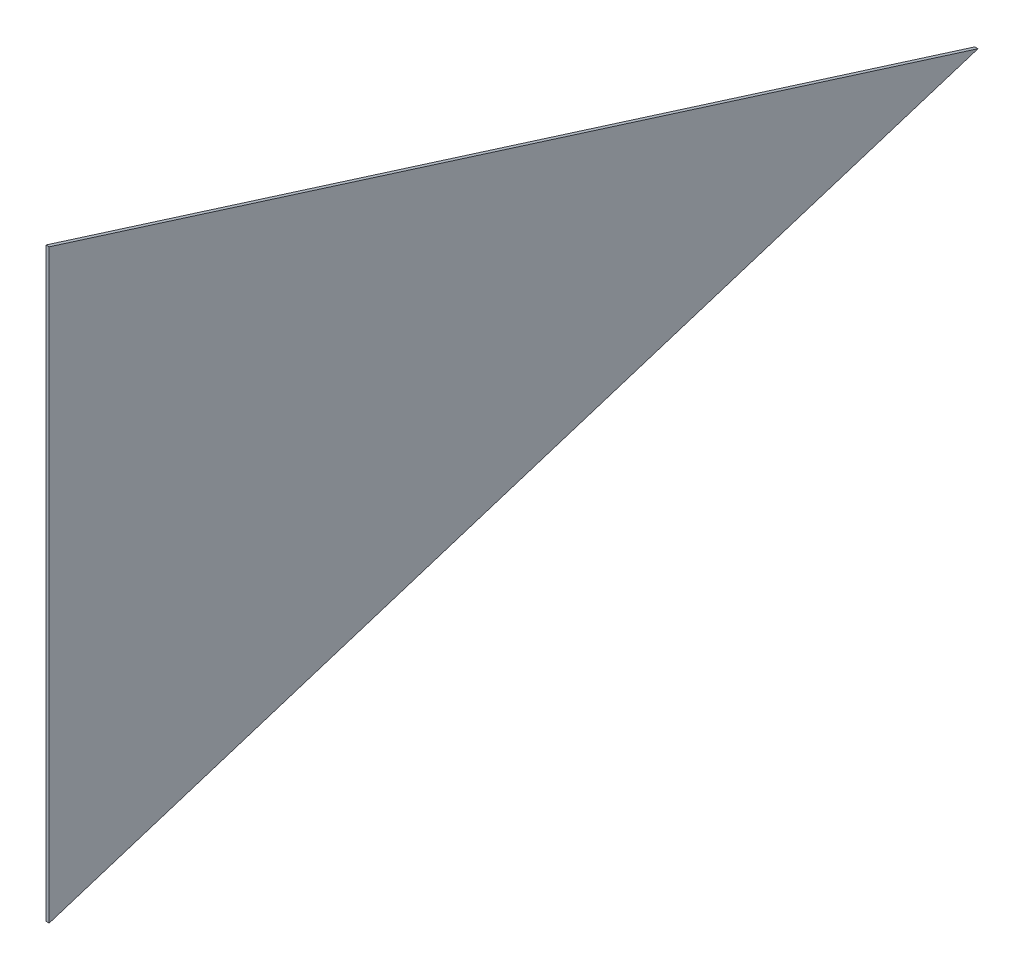
SolidWorks part; units mm, degrees
ref_plane "Front Plane" through (0, 0, 0) normal (1, 0, 0) x (0, 1, 0)
ref_plane "Top Plane" through (0, 0, 0) normal (0, 0, 1) x (0, 1, 0)
ref_plane "Right Plane" through (0, 0, 0) normal (0, 1, 0) x (-1, 0, 0)
sketch "Sketch1" plane through (0, 0, 0) normal (1, 0, 0) x (0, 1, 0)
  line L0 (0, 0) -> (-580.6227, 1841.5)
  line L1 (-580.6227, 1841.5) -> (580.6227, 1841.5)
  line L2 (580.6227, 1841.5) -> (0, 0)
  point P3 (0, 1841.5)
  dimension "D1" = 1841.5
  dimension "D2" = 35
extrude "Boss-Extrude1" add sketch "Sketch1" along normal blind 6.35
